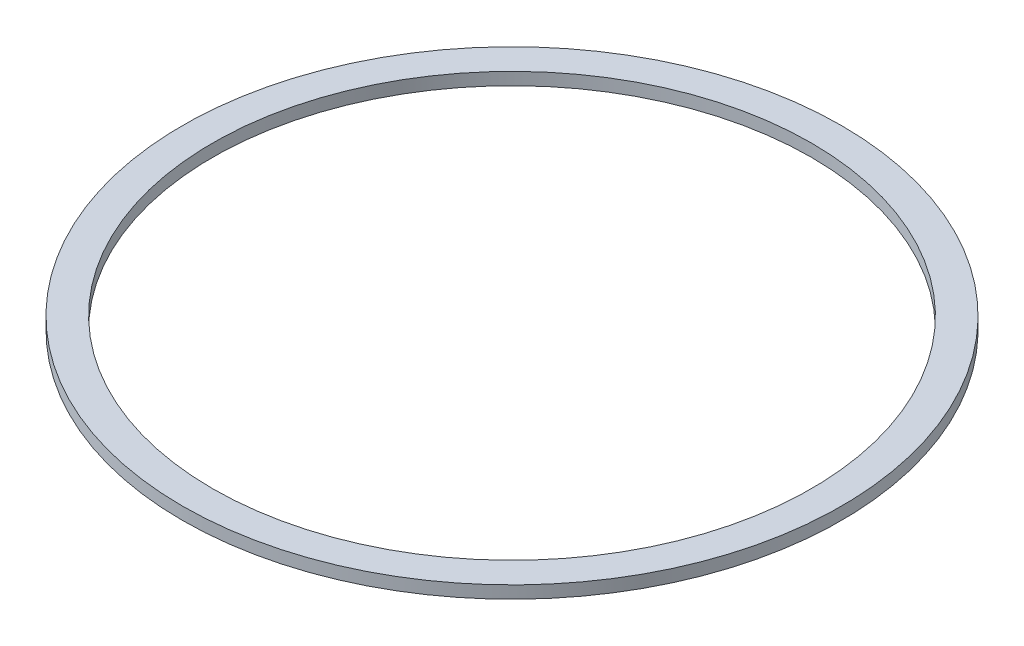
SolidWorks part; units mm, degrees
material "Thornel Mat VMA"
ref_plane "前视基准面" through (0, 0, 0) normal (0, 0, 1) x (1, 0, 0)
ref_plane "上视基准面" through (0, 0, 0) normal (0, 1, 0) x (1, 0, 0)
ref_plane "右视基准面" through (0, 0, 0) normal (1, 0, 0) x (0, 0, -1)
sketch "草图1" plane through (0, 0, 0) normal (0, 1, 0) x (1, 0, 0)
  circle A0 centre (0, 0) radius 53
  circle A1 centre (0, 0) radius 48.15
  dimension "D1" = 106
  dimension "D2" = 96.3
extrude "凸台-拉伸1" add sketch "草图1" along normal blind 2
